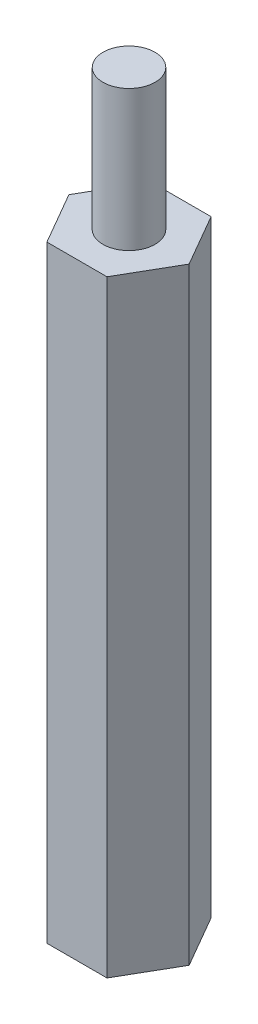
SolidWorks part; units mm, degrees
ref_plane "Front Plane" through (0, 0, 0) normal (0, 0, 1) x (1, 0, 0)
ref_plane "Top Plane" through (0, 0, 0) normal (0, 1, 0) x (1, 0, 0)
ref_plane "Right Plane" through (0, 0, 0) normal (1, 0, 0) x (0, 0, -1)
sketch "Sketch3" plane through (0, 0, 0) normal (0, 1, 0) x (1, 0, 0)
  line L1 (-3.4641, 0) -> (-1.7321, -3)
  line L2 (-1.7321, -3) -> (1.7321, -3)
  line L3 (1.7321, -3) -> (3.4641, 0)
  line L4 (3.4641, 0) -> (1.7321, 3)
  line L5 (1.7321, 3) -> (-1.7321, 3)
  line L6 (-1.7321, 3) -> (-3.4641, 0)
  circle A0 centre (0, 0) radius 3 construction
  dimension "D1" = 6
extrude "Boss-Extrude1" add sketch "Sketch3" along normal blind 35
sketch "Sketch5" plane through (0, 35, 0) normal (0, 1, 0) x (1, 0, 0)
  circle A0 centre (0, 0) radius 1.5
  dimension "D1" = 3
extrude "Boss-Extrude2" add sketch "Sketch5" along normal blind 8.0916
sketch "Sketch6" plane through (0, 0, 0) normal (0, -1, 0) x (1, 0, 0)
  circle A0 centre (0, 0) radius 1.5
extrude "Cut-Extrude1" cut sketch "Sketch6" against normal blind 4
